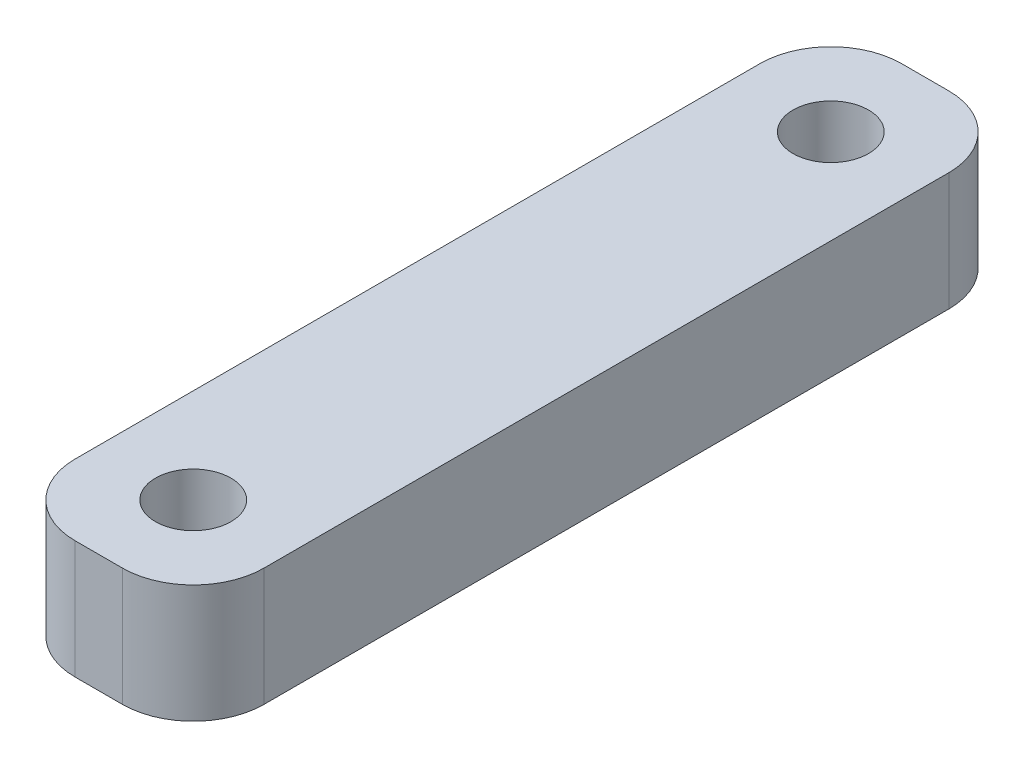
SolidWorks part; units mm, degrees
ref_plane "Front" through (0, 0, 0) normal (0, 0, 1) x (1, 0, 0)
ref_plane "Top" through (0, 0, 0) normal (0, 1, 0) x (1, 0, 0)
ref_plane "Right" through (0, 0, 0) normal (1, 0, 0) x (0, 0, -1)
sketch "Sketch1" plane through (0, 0, 0) normal (0, 0, 1) x (1, 0, 0)
  line L1 (0, 0) -> (8, 0)
  line L2 (0, 0) -> (0, -5)
  line L3 (0, -5) -> (8, -5)
  line L4 (8, 0) -> (8, -5)
  dimension "D1" = 5
  dimension "D2" = 8
extrude "Boss-Extrude1" add sketch "Sketch1" along normal blind 35
sketch "Sketch2" plane through (0, 0, 0) normal (0, 1, 0) x (1, 0, 0)
  line L0 (8, -35) -> (0, -35) construction
  line L1 (8, -35) -> (8, 0) construction
  line L2 (8, 0) -> (0, 0) construction
  circle A0 centre (4, -4) radius 1.6
  circle A1 centre (4, -31) radius 1.6
  dimension "D1" = 3.2
  dimension "D2" = 3.2
  dimension "D3" = 4
  dimension "D4" = 4
  dimension "D5" = 4
  dimension "D6" = 4
extrude "Cut-Extrude1" cut sketch "Sketch2" against normal through all
fillet "Fillet1" radius 3 4 edges at (0, -2.5, 0) (8, -2.5, 0) (0, -2.5, 35) (8, -2.5, 35)
